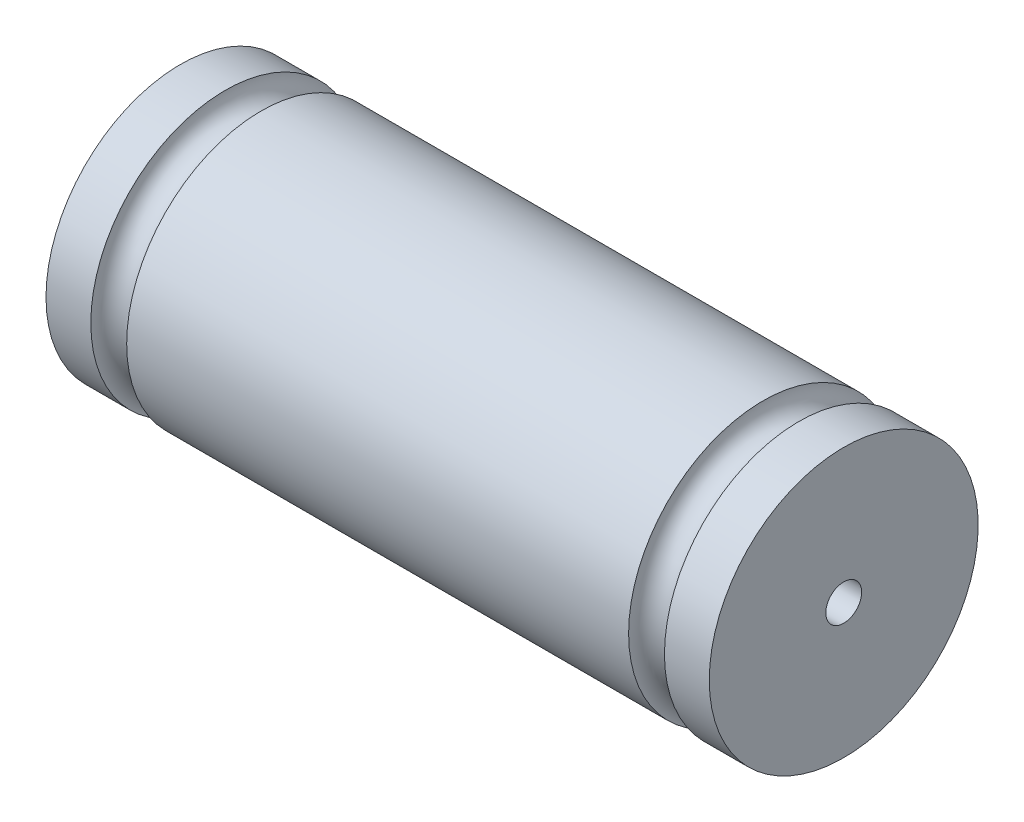
SolidWorks part; units mm, degrees
ref_plane "前视基准面" through (0, 0, 0) normal (0, 0, 1) x (1, 0, 0)
ref_plane "上视基准面" through (0, 0, 0) normal (0, 1, 0) x (1, 0, 0)
ref_plane "右视基准面" through (0, 0, 0) normal (1, 0, 0) x (0, 0, -1)
other "Configuration Table"
sketch "草图1" plane through (0, 0, 0) normal (0, 0, 1) x (1, 0, 0)
  line L0 (0, 0) -> (4679.521, 0) construction
  line L1 (0, 0) -> (0, -4679.521) construction
  line L2 (30, 4.2421) -> (30, -4675.2789) construction
  line L3 (-30, 4.1704) -> (-30, -4675.3506) construction
  line L4 (-24.9643, 10) -> (49975.0357, 10) construction
  line L5 (-35.4078, 15) -> (49964.5922, 15) construction
  line L6 (-40, 7.6445) -> (-40, -49992.3555) construction
  line L7 (40, 5.4741) -> (40, -49994.5259) construction
  line L8 (-32, 15) -> (-37, 15)
  line L12 (37, 15) -> (32, 15)
  line L13 (-28, 15) -> (28, 15)
  line L14 (-46.6505, 2) -> (49953.3495, 2) construction
  line L15 (-37, 2) -> (37, 2)
  line L16 (-37, 29.0356) -> (-37, -49970.9644) construction
  line L17 (37, 28.6151) -> (37, -49971.3849) construction
  line L18 (37, 15) -> (37, 2)
  line L19 (-37, 15) -> (-37, 2)
  arc A0 (-32, 15) -> (-28, 15) centre (-30, 15) ccw
  arc A1 (28, 15) -> (32, 15) centre (30, 15) ccw
  point P34 (-30, 15)
  point P35 (30, 15)
  dimension "D7" = 2
  dimension "D8" = 2
  dimension "D1" = 30
  dimension "D2" = 30
  dimension "D3" = 10
  dimension "D4" = 15
  dimension "D5" = 10
  dimension "D6" = 10
  dimension "D9" = 2
  dimension "D10" = 3
  dimension "D11" = 3
revolve "旋转2" add sketch "草图1" angle 360 about L0
sketch "草图3" plane through (0, 0, 0) normal (0, 0, 1) x (1, 0, 0)
  line L0 (0, 0) -> (50000, 0) construction
  arc A0 (-32, 15) -> (-28, 15) centre (-30, 15) ccw construction
  arc A1 (28, 15) -> (32, 15) centre (30, 15) ccw construction
  point P0 (-30, 13)
  point P1 (30, 13)
